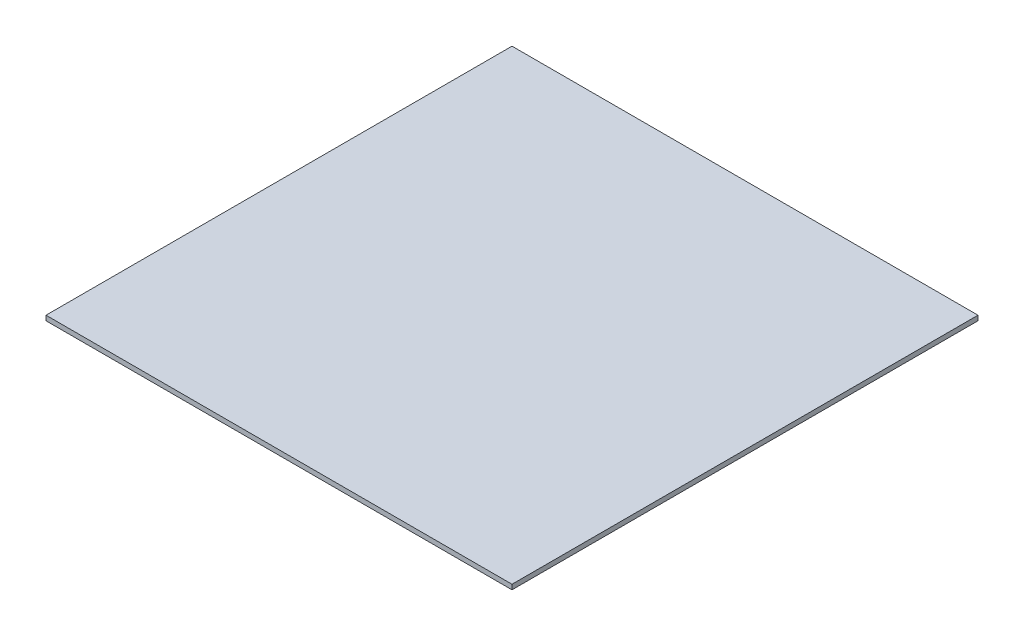
SolidWorks part; units mm, degrees
ref_plane "Front Plane" through (0, 0, 0) normal (0, 0, 1) x (1, 0, 0)
ref_plane "Top Plane" through (0, 0, 0) normal (0, 1, 0) x (1, 0, 0)
ref_plane "Right Plane" through (0, 0, 0) normal (1, 0, 0) x (0, 0, -1)
sketch "Sketch1" plane through (0, 0, 0) normal (0, 1, 0) x (1, 0, 0)
  line L1 (-387.1576, 281.7091) -> (222.4424, 281.7091)
  line L2 (-387.1576, 281.7091) -> (-387.1576, -327.8909)
  line L3 (-387.1576, -327.8909) -> (222.4424, -327.8909)
  line L4 (222.4424, 281.7091) -> (222.4424, -327.8909)
  dimension "D1" = 609.6
  dimension "D2" = 609.6
extrude "Boss-Extrude1" add sketch "Sketch1" along normal blind 6.35
